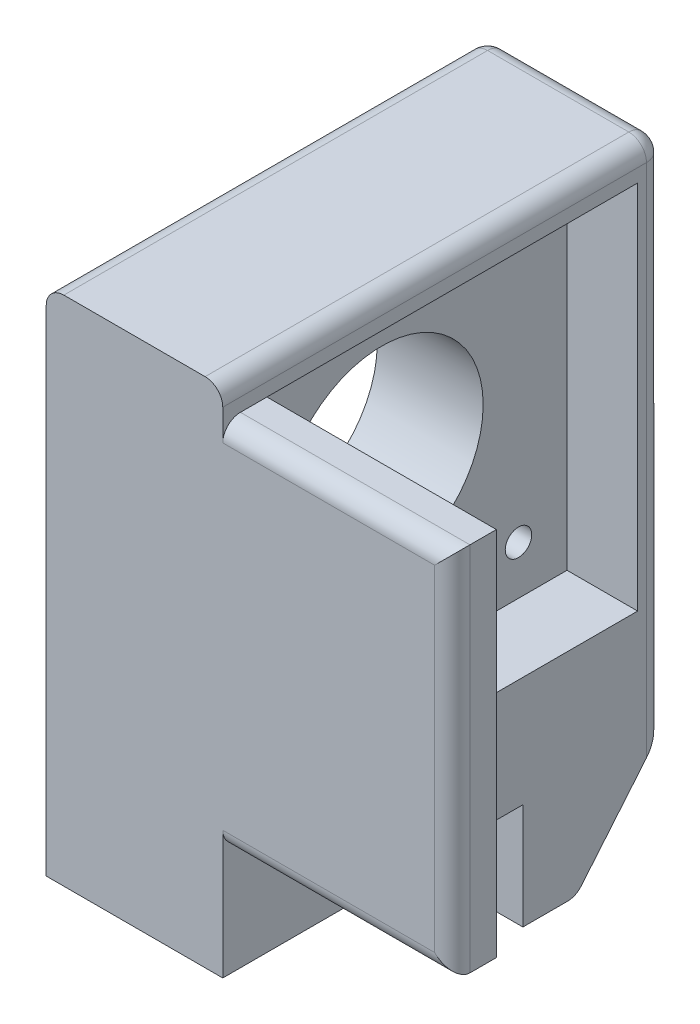
SolidWorks part; units mm, degrees
ref_plane "Front Plane" through (0, 0, 0) normal (0, 0, 1) x (1, 0, 0)
ref_plane "Top Plane" through (0, 0, 0) normal (0, 1, 0) x (1, 0, 0)
ref_plane "Right Plane" through (0, 0, 0) normal (1, 0, 0) x (0, 0, -1)
sketch "Sketch1" plane through (0, 0, 0) normal (0, 1, 0) x (1, 0, 0)
  line L1 (0, 0) -> (-20, 0)
  line L2 (0, 0) -> (0, -50)
  line L3 (0, -50) -> (-20, -50)
  line L4 (-20, 0) -> (-20, -50)
  dimension "D1" = 20
  dimension "D2" = 50
extrude "Boss-Extrude1" add sketch "Sketch1" along normal blind 70
sketch "Sketch2" plane through (0, 0, 0) normal (1, 0, 0) x (0, 0, -1)
  line L0 (-50, 70) -> (0, 70) construction
  line L1 (0, 70) -> (0, 0) construction
  line L2 (0, 45.5) -> (-50, 45.5) construction
  line L3 (-24, 70) -> (-24, 0) construction
  line L4 (-24, 70) -> (-24, 0) construction
  line L5 (-50, 0) -> (0, 0) construction
  line L7 (-50, 70) -> (-50, 0) construction
  circle A0 centre (-8.5, 61) radius 1.5
  circle A4 centre (-24, 45.5) radius 11.5
  circle A5 centre (-8.5, 30) radius 1.5
  circle A8 centre (-39.5, 30) radius 1.5
  circle A9 centre (-39.5, 61) radius 1.5
  point P24 (-25, 0)
  dimension "D1" = 3
  dimension "D2" = 9
  dimension "D3" = 15.5
  dimension "D6" = 23
  dimension "D7" = 0
  dimension "D8" = 0
  dimension "D4" = 15.5
  dimension "D9" = 1
  dimension "D5" = 0
extrude "Cut-Extrude2" cut sketch "Sketch2" against normal blind 60
sketch "Sketch4" plane through (0, 0, 0) normal (1, 0, 0) x (0, 0, -1)
  line L0 (0, 70) -> (0, 0) construction
  line L1 (-50, 0) -> (-16, 0)
  line L2 (-50, 0) -> (-50, 12)
  line L3 (-50, 12) -> (-16, 12)
  line L4 (-16, 0) -> (-16, 12)
  dimension "D1" = 12
  dimension "D2" = 16
extrude "Cut-Extrude3" cut sketch "Sketch4" against normal blind 60
sketch "Sketch8" plane through (0, 0, 0) normal (0, 0, -1) x (-1, 0, 0)
  line L0 (0, 0) -> (20, 0) construction
  line L1 (20, 70) -> (20, 0) construction
  line L2 (0, 70) -> (0, 0) construction
  circle A0 centre (15, 6) radius 2
  circle A1 centre (5, 6) radius 2
  dimension "D1" = 4
  dimension "D2" = 6
  dimension "D3" = 5
  dimension "D4" = 4
  dimension "D5" = 0
  dimension "D6" = 5
extrude "Cut-Extrude5" cut sketch "Sketch8" against normal blind 15
sketch "Sketch9" plane through (0, 0, 0) normal (1, 0, 0) x (0, 0, -1)
  line L0 (0, 49.6538) -> (-50, 41) construction
  line L1 (-3, 66.5) -> (-45, 66.5)
  line L2 (-3, 66.5) -> (-3, 24.5)
  line L3 (-3, 24.5) -> (-45, 24.5)
  line L4 (-45, 66.5) -> (-45, 24.5)
  line L5 (0, 70) -> (0, 0) construction
  line L6 (-50, 70) -> (-50, 12) construction
  line L7 (-24, 70) -> (-24, 12) construction
  line L8 (-50, 70) -> (0, 70) construction
  line L9 (-16, 12) -> (-50, 12) construction
  circle A0 centre (-24, 45.5) radius 11.5 construction
  dimension "D1" = 0
  dimension "D2" = 42
  dimension "D3" = 21
  dimension "D4" = 42
  dimension "D5" = 21
  dimension "D6" = 0
extrude "Cut-Extrude6" cut sketch "Sketch9" against normal blind 8
sketch "Sketch11" plane through (0, 0, 0) normal (1, 0, 0) x (0, 0, -1)
  line L7 (-10, 0) -> (0, 0)
  line L8 (-16, 0) -> (0, 0) construction
  line L9 (0, 0) -> (0, 12)
  line L10 (0, 70) -> (0, 0) construction
  line L11 (0, 12) -> (-10, 0)
  line L12 (-16, 12) -> (-50, 12) construction
  dimension "D1" = 0
  dimension "D2" = 6
extrude "Cut-Extrude8" cut sketch "Sketch11" against normal blind 30
sketch "Sketch17" plane through (0, 0, 0) normal (0, 0, -1) x (-1, 0, 0)
  circle A0 centre (15, 6) radius 3.5
  circle A1 centre (5, 6) radius 3.5
  dimension "D1" = 7
  dimension "D2" = 7
extrude "Cut-Extrude13" cut sketch "Sketch17" against normal blind 9.1811
sketch "Sketch18" plane through (-20, 0, 0) normal (-1, 0, 0) x (0, 0, 1)
  line L0 (50, 70) -> (50, 12) construction
  circle A0 centre (46, 20) radius 1.5
  circle A1 centre (39.5, 30) radius 1.5 construction
  circle A2 centre (39, 20) radius 1.5
  dimension "D1" = 3
  dimension "D2" = 10
  dimension "D3" = 4
  dimension "D4" = 3
  dimension "D5" = 0
  dimension "D6" = 7
extrude "Cut-Extrude14" cut sketch "Sketch18" against normal blind 7
fillet "Fillet1" radius 2 1 edges at (-20, 41, 0)
fillet "Fillet2" radius 2 3 edges at (-9, 70, 0) (-19.4142, 70, 0.5858) (-20, 70, 26)
fillet "Fillet3" radius 2 3 edges at (0, 40, 0) (0, 69.4142, 0.5858) (0, 70, 26)
fillet "Fillet4" radius 2 1 edges at (-10, 0, 10)
sketch "Sketch19" plane through (0, 0, 0) normal (1, 0, 0) x (0, 0, -1)
  line L0 (-50, 68) -> (-50, 12) construction
  line L1 (-45, 66.5) -> (-50, 66.5)
  line L2 (-45, 66.5) -> (-45, 24.5)
  line L3 (-45, 24.5) -> (-50, 24.5)
  line L4 (-50, 66.5) -> (-50, 24.5)
  line L5 (-45, 24.5) -> (-3, 24.5) construction
  dimension "D1" = 0
extrude "Boss-Extrude2" add sketch "Sketch19" along normal blind 26
fillet "Fillet6" radius 2 3 edges at (13, 66.5, 50) (26, 45.5, 50) (13, 24.5, 50)
